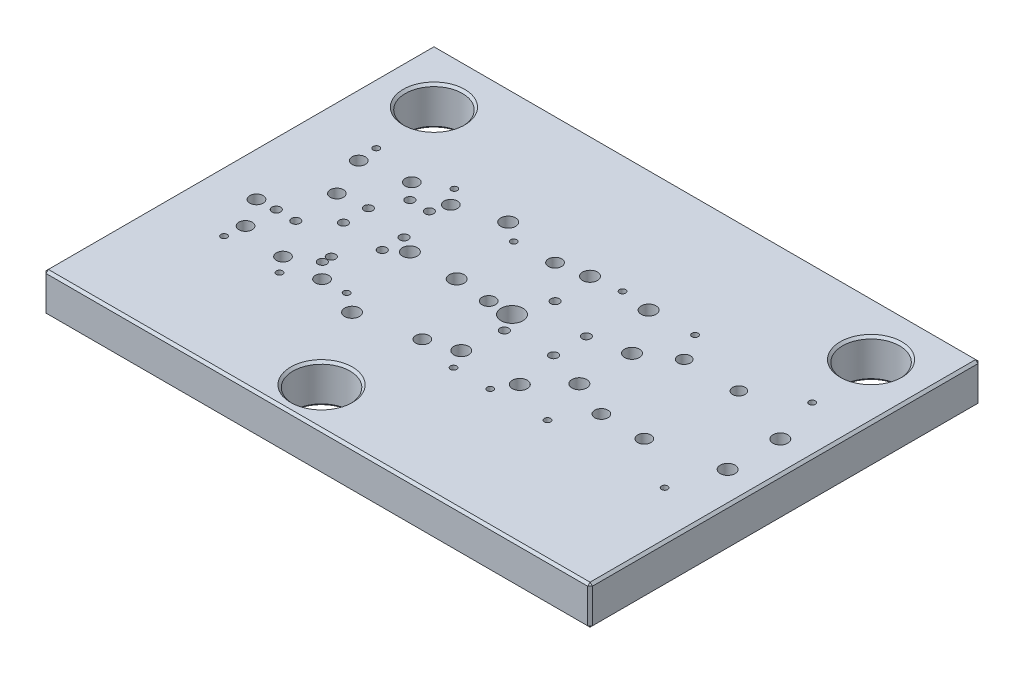
SolidWorks part; units mm, degrees
material "Plain Carbon Steel"
ref_plane "Front Plane" through (0, 0, 0) normal (0, 0, 1) x (1, 0, 0)
ref_plane "Top Plane" through (0, 0, 0) normal (0, 1, 0) x (1, 0, 0)
ref_plane "Right Plane" through (0, 0, 0) normal (1, 0, 0) x (0, 0, -1)
sketch "Sketch1" plane through (0, 0, 0) normal (0, 1, 0) x (1, 0, 0)
  line L1 (-350, -250) -> (350, -250)
  line L2 (-350, -250) -> (-350, 250)
  line L3 (-350, 250) -> (350, 250)
  line L4 (350, -250) -> (350, 250)
  line L5 (-350, -250) -> (350, 250) construction
  line L6 (-350, 250) -> (350, -250) construction
  point P0 (0, 0)
  dimension "D1" = 700
  dimension "D2" = 500
extrude "Boss-Extrude1" add sketch "Sketch1" against normal blind 50
sketch "Sketch2" plane through (0, 0, 0) normal (0, 1, 0) x (1, 0, 0)
  line L0 (350, 250) -> (-350, 250) construction
  line L1 (-350, 250) -> (-350, -250) construction
  line L2 (350, -250) -> (350, 250) construction
  line L3 (-350, -250) -> (350, -250) construction
  circle A0 centre (-280, 180) radius 36.5
  circle A1 centre (280, 180) radius 36.5
  circle A2 centre (-44, -200) radius 36.5
  dimension "D1" = 73
  dimension "D2" = 70
  dimension "D3" = 70
  dimension "D4" = 70
  dimension "D5" = 50
  dimension "D6" = 44
extrude "Cut-Extrude1" cut sketch "Sketch2" against normal up to next
chamfer "Chamfer1" distance 3 angle 45 6 edges at (280, -50, -216.5) (280, 0, -143.5) (-280, -50, -216.5) (-280, 0, -143.5) (-44, -50, 163.5) (-44, 0, 236.5)
chamfer "Chamfer2" distance 3 angle 45 12 edges at (-350, -25, -250) (-350, -25, 250) (350, -25, -250) (0, -50, -250) (-350, -50, 0) (0, -50, 250) (350, -50, 0) (350, -25, 250) (350, 0, 0) (0, 0, -250) (-350, 0, 0) (0, 0, 250)
hole_wizard "M30x2.0 Tapped Hole1" positions "Sketch5" profile "Sketch4" tap size "M30x2.0" standard "ISO" end condition through all
sketch "Sketch5" plane through (0, 0, 0) normal (0, 1, 0) x (1, 0, 0)
  point P0 (0, 0)
sketch "Sketch4" plane through (0, 0, 0) normal (1, 0, 0) x (0, 0, 1)
  line L0 (0, 0) -> (0, 50)
  line L1 (0, 50) -> (14, 50)
  line L2 (14, 50) -> (14, 0)
  line L5 (14, 0) -> (0, 0)
  line L11 (0, -6.35) -> (0, 107.95) construction
  dimension "Thru Tap Drill Dia." = 28
  dimension "Thru Tap Drill Depth" = 50
cosmetic thread "Hole Thread1"
sketch "Sketch7" plane through (0, 0, 0) normal (0, 1, 0) x (1, 0, 0)
  circle A0 centre (310, 33.75) radius 6
  circle A1 centre (310, -33.75) radius 6
  circle A2 centre (120, -33.75) radius 6
  circle A3 centre (120, 33.75) radius 6
  dimension "D1" = 12
extrude "Cut-Extrude2" cut sketch "Sketch7" against normal up to next
sketch "Sketch8" plane through (0, 0, 0) normal (0, 1, 0) x (1, 0, 0)
  circle A0 centre (222.63, -53.14) radius 8.5
  circle A1 centre (167.63, -53.14) radius 8.5
  dimension "D1" = 17
extrude "Cut-Extrude3" cut sketch "Sketch8" against normal up to next
sketch "Sketch9" plane through (0, 0, 0) normal (0, 1, 0) x (1, 0, 0)
  circle A0 centre (160.13, 60.5) radius 8
  circle A1 centre (230.13, 60.5) radius 8
  dimension "D1" = 16
extrude "Cut-Extrude4" cut sketch "Sketch9" against normal up to next
sketch "Sketch11" plane through (0, 0, 0) normal (0, 1, 0) x (1, 0, 0)
  circle A0 centre (310, -33.75) radius 9.5
  circle A1 centre (310, 33.75) radius 9.5
  circle A2 centre (120, -33.75) radius 9.5
  circle A3 centre (120, 33.75) radius 9.5
  dimension "D1" = 19
extrude "Cut-Extrude5" cut sketch "Sketch11" against normal blind 36.8
hole_wizard "M10 Tapped Hole1" positions "Sketch14" profile "Sketch13" tap size "M10" standard "ISO"
sketch "Sketch14" plane through (0, -50, 0) normal (0, -1, 0) x (-1, 0, 0)
  point P0 (-307, -94.5)
  point P3 (-123, -94.5)
  point P6 (-123, 94.5)
  point P9 (-307, 94.5)
sketch "Sketch13" plane through (307, -50, 94.5) normal (1, 0, 0) x (0, 0, -1)
  line L0 (0, 0) -> (0, 30.0537)
  line L1 (0, 30.0537) -> (4.25, 27.5)
  line L2 (4.25, 27.5) -> (4.25, 0)
  line L5 (4.25, 0) -> (0, 0)
  line L10 (0, 30.0537) -> (-4.25, 27.5) construction
  line L11 (0, -6.35) -> (0, 107.95) construction
  dimension "Tap Drill Dia." = 8.5
  dimension "Tap Drill Depth" = 27.5
  dimension "Drill Angle" = 118
cosmetic thread "Hole Thread2"
cosmetic thread "Hole Thread3"
cosmetic thread "Hole Thread4"
cosmetic thread "Hole Thread5"
hole_wizard "Ø8.0mm Dowel Hole1" positions "Sketch17" profile "Sketch16" hole size "Ø8.0" standard "ISO" end condition through all
sketch "Sketch17" plane through (0, 0, 0) normal (0, 1, 0) x (1, 0, 0)
  point P0 (290, 94.5)
  point P3 (140, 94.5)
  point P6 (290, -94.5)
  point P9 (140, -94.5)
sketch "Sketch16" plane through (290, 0, -94.5) normal (1, 0, 0) x (0, 0, 1)
  line L0 (0, 0) -> (0, 50)
  line L1 (0, 50) -> (4, 50)
  line L2 (4, 50) -> (4, 0)
  line L5 (4, 0) -> (0, 0)
  line L11 (0, -6.35) -> (0, 107.95) construction
  dimension "Thru Hole Dia." = 8
  dimension "Thru Hole Depth" = 50
hole_wizard "M8 Tapped Hole1" positions "Sketch20" profile "Sketch19" tap size "M8" standard "ISO"
sketch "Sketch20" plane through (0, -50, 0) normal (0, 1, 0) x (1, 0, 0)
  point P0 (62.13, 96.5)
  point P3 (28.13, 96.5)
  point P6 (84.13, -96.5)
  point P9 (6.13, -96.5)
sketch "Sketch19" plane through (62.13, -50, -96.5) normal (1, 0, 0) x (0, 0, -1)
  line L0 (0, 0) -> (0, 24.2929)
  line L1 (0, 24.2929) -> (3.4, 22.25)
  line L2 (3.4, 22.25) -> (3.4, 0)
  line L5 (3.4, 0) -> (0, 0)
  line L10 (0, 24.2929) -> (-3.4, 22.25) construction
  line L11 (0, -6.35) -> (0, 107.95) construction
  dimension "Tap Drill Dia." = 6.8
  dimension "Tap Drill Depth" = 22.25
  dimension "Drill Angle" = 118
cosmetic thread "Hole Thread6"
cosmetic thread "Hole Thread7"
cosmetic thread "Hole Thread8"
cosmetic thread "Hole Thread9"
hole_wizard "Ø8.0mm Dowel Hole2" positions "Sketch23" profile "Sketch22" hole size "Ø8.0" standard "ISO" end condition through all
sketch "Sketch23" plane through (0, 0, 0) normal (0, 1, 0) x (1, 0, 0)
  point P0 (68.63, -96.5)
  point P3 (21.63, -96.5)
  point P6 (45.13, 96.5)
sketch "Sketch22" plane through (68.63, 0, 96.5) normal (1, 0, 0) x (0, 0, 1)
  line L0 (0, 0) -> (0, 50)
  line L1 (0, 50) -> (4, 50)
  line L2 (4, 50) -> (4, 0)
  line L5 (4, 0) -> (0, 0)
  line L11 (0, -6.35) -> (0, 107.95) construction
  dimension "Thru Hole Dia." = 8
  dimension "Thru Hole Depth" = 50
hole_wizard "Ø11.0 (11) Diameter Hole1" positions "Sketch26" profile "Sketch25" hole size "Ø11.0" standard "ISO" end condition through all
sketch "Sketch26" plane through (0, 0, 0) normal (0, 1, 0) x (1, 0, 0)
  point P0 (71.88, -18.64)
  point P3 (12.88, -22.64)
  point P6 (71.88, 23.36)
  point P9 (12.88, 42.36)
sketch "Sketch25" plane through (71.88, 0, 18.64) normal (1, 0, 0) x (0, 0, 1)
  line L0 (0, 0) -> (0, 50)
  line L1 (0, 50) -> (5.5, 50)
  line L2 (5.5, 50) -> (5.5, 0)
  line L5 (5.5, 0) -> (0, 0)
  line L11 (0, -6.35) -> (0, 107.95) construction
  dimension "Thru Hole Dia." = 11
  dimension "Thru Hole Depth" = 50
sketch "Sketch27" plane through (0, 0, 0) normal (0, 1, 0) x (1, 0, 0)
  circle A0 centre (7.63, 92.36) radius 6
  circle A1 centre (82.63, 92.36) radius 6
  circle A2 centre (82.63, -72.64) radius 6
  circle A3 centre (7.63, -72.64) radius 6
  dimension "D1" = 12
extrude "Cut-Extrude6" cut sketch "Sketch27" against normal through all
sketch "Sketch29" plane through (0, 0, 0) normal (0, 1, 0) x (1, 0, 0)
  circle A0 centre (7.63, 92.36) radius 9.5
  circle A1 centre (82.63, 92.36) radius 9.5
  circle A2 centre (7.63, -72.64) radius 9.5
  circle A3 centre (82.63, -72.64) radius 9.5
  dimension "D1" = 19
extrude "Cut-Extrude7" cut sketch "Sketch29" against normal blind 36.8
sketch "Sketch30" plane through (0, 0, 0) normal (0, 1, 0) x (1, 0, 0)
  circle A0 centre (-29.87, 85) radius 5
  circle A1 centre (-29.87, 0) radius 5
  circle A2 centre (-29.87, -85) radius 5
  dimension "D1" = 10
extrude "Cut-Extrude8" cut sketch "Sketch30" against normal through all
sketch "Sketch31" plane through (0, 0, 0) normal (0, 1, 0) x (1, 0, 0)
  circle A0 centre (-29.87, 85) radius 8.5
  circle A1 centre (-29.87, 0) radius 8.5
  circle A2 centre (-29.87, -85) radius 8.5
  dimension "D1" = 17
extrude "Cut-Extrude9" cut sketch "Sketch31" against normal blind 39.8
hole_wizard "M8 Tapped Hole2" positions "Sketch34" profile "Sketch33" tap size "M8" standard "ISO"
sketch "Sketch34" plane through (0, -50, 0) normal (0, -1, 0) x (-1, 0, 0)
  point P0 (79.87, -97.5)
  point P3 (129.87, -97.5)
  point P6 (79.87, 97.5)
  point P9 (129.87, 97.5)
sketch "Sketch33" plane through (-79.87, -50, 97.5) normal (1, 0, 0) x (0, 0, -1)
  line L0 (0, 0) -> (0, 24.2929)
  line L1 (0, 24.2929) -> (3.4, 22.25)
  line L2 (3.4, 22.25) -> (3.4, 0)
  line L5 (3.4, 0) -> (0, 0)
  line L10 (0, 24.2929) -> (-3.4, 22.25) construction
  line L11 (0, -6.35) -> (0, 107.95) construction
  dimension "Tap Drill Dia." = 6.8
  dimension "Tap Drill Depth" = 22.25
  dimension "Drill Angle" = 118
cosmetic thread "Hole Thread10"
cosmetic thread "Hole Thread11"
cosmetic thread "Hole Thread12"
cosmetic thread "Hole Thread13"
hole_wizard "Ø8.0mm Dowel Hole3" positions "Sketch37" profile "Sketch36" hole size "Ø8.0" standard "ISO" end condition through all
sketch "Sketch37" plane through (0, 0, 0) normal (0, 1, 0) x (1, 0, 0)
  point P0 (-79.87, 81.975)
  point P3 (-129.87, -82)
sketch "Sketch36" plane through (-79.87, 0, -81.975) normal (1, 0, 0) x (0, 0, 1)
  line L0 (0, 0) -> (0, 50)
  line L1 (0, 50) -> (4, 50)
  line L2 (4, 50) -> (4, 0)
  line L5 (4, 0) -> (0, 0)
  line L11 (0, -6.35) -> (0, 107.95) construction
  dimension "Thru Hole Dia." = 8
  dimension "Thru Hole Depth" = 50
sketch "Sketch38" plane through (0, 0, 0) normal (0, 1, 0) x (1, 0, 0)
  circle A0 centre (-104.87, 100) radius 6 construction
  circle A1 centre (-104.87, -100) radius 6 construction
  circle A2 centre (-104.87, 100) radius 6
  circle A3 centre (-104.87, -100) radius 6
  circle A4 centre (-74.87, 4) radius 6 construction
  circle A5 centre (-74.87, 4) radius 6
  circle A6 centre (-134.87, 4) radius 6 construction
  circle A7 centre (-134.87, 4) radius 6
extrude "Cut-Extrude10" cut sketch "Sketch38" against normal through all
sketch "Sketch39" plane through (0, 0, 0) normal (0, 1, 0) x (1, 0, 0)
  circle A0 centre (-104.87, 100) radius 9.5
  circle A1 centre (-104.87, -100) radius 9.5
  circle A2 centre (-74.87, 4) radius 9.5
  circle A3 centre (-134.87, 4) radius 9.5
  dimension "D1" = 19
extrude "Cut-Extrude11" cut sketch "Sketch39" against normal blind 36.8
sketch "Sketch40" plane through (0, -50, 0) normal (0, -1, 0) x (1, 0, 0)
  circle A0 centre (-185.87, -82.5) radius 10 construction
  circle A1 centre (-210.87, 82.5) radius 10 construction
  circle A2 centre (-185.87, 82.5) radius 10 construction
  circle A3 centre (-160.87, 82.5) radius 10 construction
  circle A4 centre (-160.87, 33) radius 10 construction
  circle A5 centre (-210.87, 33) radius 10 construction
  circle A6 centre (-160.87, -39) radius 10 construction
  circle A7 centre (-160.87, -82.5) radius 10 construction
  circle A8 centre (-210.87, -82.5) radius 10 construction
  circle A9 centre (-210.87, -47) radius 10 construction
  circle A10 centre (-185.87, -82.5) radius 10
  circle A11 centre (-210.87, 82.5) radius 10
  circle A12 centre (-185.87, 82.5) radius 10
  circle A13 centre (-160.87, 82.5) radius 10
  circle A14 centre (-160.87, 33) radius 10
  circle A15 centre (-210.87, 33) radius 10
  circle A16 centre (-160.87, -39) radius 10
  circle A17 centre (-160.87, -82.5) radius 10
  circle A18 centre (-210.87, -82.5) radius 10
  circle A19 centre (-210.87, -47) radius 10
extrude "Cut-Extrude12" cut sketch "Sketch40" against normal blind 9.2
hole_wizard "Ø10.0 (10) Diameter Hole1" positions "Sketch44" profile "Sketch43" hole size "Ø10.0" standard "ISO" end condition through all
sketch "Sketch44" plane through (0, 0, 0) normal (0, 1, 0) x (1, 0, 0)
  point P0 (-160.87, 82.5)
  point P3 (-210.87, 82.5)
  point P6 (-160.87, -82.5)
  point P9 (-210.87, -82.5)
sketch "Sketch43" plane through (-160.87, 0, -82.5) normal (1, 0, 0) x (0, 0, 1)
  line L0 (0, 0) -> (0, 50)
  line L1 (0, 50) -> (5, 50)
  line L2 (5, 50) -> (5, 0)
  line L5 (5, 0) -> (0, 0)
  line L11 (0, -6.35) -> (0, 107.95) construction
  dimension "Thru Hole Dia." = 10
  dimension "Thru Hole Depth" = 50
sketch "Sketch45" plane through (0, 0, 0) normal (0, 1, 0) x (1, 0, 0)
  circle A0 centre (-160.87, 82.5) radius 8.5
  circle A1 centre (-210.87, 82.5) radius 8.5
  circle A2 centre (-160.87, -82.5) radius 8.5
  circle A3 centre (-210.87, -82.5) radius 8.5
  dimension "D1" = 17
extrude "Cut-Extrude13" cut sketch "Sketch45" against normal blind 33.8
hole_wizard "Ø11.0 (11) Diameter Hole2" positions "Sketch48" profile "Sketch47" hole size "Ø11.0" standard "ISO" end condition through all
sketch "Sketch48" plane through (0, 0, 0) normal (0, 1, 0) x (1, 0, 0)
  point P0 (-167.37, 61.5)
  point P3 (-192.37, 61.5)
  point P6 (-154.62, 16.36)
  point P9 (-209.87, 25.86)
  point P12 (-209.87, -6.14)
  point P15 (-179.87, -51.64)
  point P20 (-179.87, -63.14)
  point P23 (-154.62, -11.64)
sketch "Sketch47" plane through (-167.37, 0, -61.5) normal (1, 0, 0) x (0, 0, 1)
  line L0 (0, 0) -> (0, 50)
  line L1 (0, 50) -> (5.5, 50)
  line L2 (5.5, 50) -> (5.5, 0)
  line L5 (5.5, 0) -> (0, 0)
  line L11 (0, -6.35) -> (0, 107.95) construction
  dimension "Thru Hole Dia." = 11
  dimension "Thru Hole Depth" = 50
hole_wizard "M8 Tapped Hole3" positions "Sketch53" profile "Sketch52" tap size "M8" standard "ISO"
sketch "Sketch53" plane through (0, -50, 0) normal (0, -1, 0) x (-1, 0, 0)
  point P0 (160.87, -102.5)
  point P3 (210.87, -102.5)
  point P6 (160.87, 102.5)
  point P9 (210.87, 102.5)
sketch "Sketch52" plane through (-160.87, -50, 102.5) normal (1, 0, 0) x (0, 0, -1)
  line L0 (0, 0) -> (0, 24.2929)
  line L1 (0, 24.2929) -> (3.4, 22.25)
  line L2 (3.4, 22.25) -> (3.4, 0)
  line L5 (3.4, 0) -> (0, 0)
  line L10 (0, 24.2929) -> (-3.4, 22.25) construction
  line L11 (0, -6.35) -> (0, 107.95) construction
  dimension "Tap Drill Dia." = 6.8
  dimension "Tap Drill Depth" = 22.25
  dimension "Drill Angle" = 118
cosmetic thread "Hole Thread14"
cosmetic thread "Hole Thread15"
cosmetic thread "Hole Thread16"
cosmetic thread "Hole Thread17"
hole_wizard "Ø8.0mm Dowel Hole4" positions "Sketch56" profile "Sketch55" hole size "Ø8.0" standard "ISO" end condition through all
sketch "Sketch56" plane through (0, 0, 0) normal (0, 1, 0) x (1, 0, 0)
  point P0 (-176.37, 102.5)
  point P3 (-195.37, -102.5)
sketch "Sketch55" plane through (-176.37, 0, -102.5) normal (1, 0, 0) x (0, 0, 1)
  line L0 (0, 0) -> (0, 50)
  line L1 (0, 50) -> (4, 50)
  line L2 (4, 50) -> (4, 0)
  line L5 (4, 0) -> (0, 0)
  line L11 (0, -6.35) -> (0, 107.95) construction
  dimension "Thru Hole Dia." = 8
  dimension "Thru Hole Depth" = 50
sketch "Sketch57" plane through (0, 0, 0) normal (0, 1, 0) x (1, 0, 0)
  circle A0 centre (-268.87, -72.5) radius 5 construction
  circle A1 centre (-291.37, -36) radius 5 construction
  circle A2 centre (-246.37, 22) radius 5 construction
  circle A3 centre (-268.87, 72.5) radius 5 construction
  circle A4 centre (-268.87, -72.5) radius 5
  circle A5 centre (-291.37, -36) radius 5
  circle A6 centre (-246.37, 22) radius 5
  circle A7 centre (-268.87, 72.5) radius 5
extrude "Cut-Extrude14" cut sketch "Sketch57" against normal through all
sketch "Sketch58" plane through (0, 0, 0) normal (0, 1, 0) x (1, 0, 0)
  circle A0 centre (-268.87, 72.5) radius 8.5
  circle A1 centre (-246.37, 22) radius 8.5
  circle A2 centre (-291.37, -36) radius 8.5
  circle A3 centre (-268.87, -72.5) radius 8.5
  dimension "D1" = 17
extrude "Cut-Extrude15" cut sketch "Sketch58" against normal blind 36.8
hole_wizard "Ø11.0 (11) Diameter Hole3" positions "Sketch61" profile "Sketch60" hole size "Ø11.0" standard "ISO" end condition through all
sketch "Sketch61" plane through (0, 0, 0) normal (0, 1, 0) x (1, 0, 0)
  point P0 (-267.37, -34.64)
  point P3 (-242.37, -34.64)
sketch "Sketch60" plane through (-267.37, 0, 34.64) normal (1, 0, 0) x (0, 0, 1)
  line L0 (0, 0) -> (0, 50)
  line L1 (0, 50) -> (5.5, 50)
  line L2 (5.5, 50) -> (5.5, 0)
  line L5 (5.5, 0) -> (0, 0)
  line L11 (0, -6.35) -> (0, 107.95) construction
  dimension "Thru Hole Dia." = 11
  dimension "Thru Hole Depth" = 50
hole_wizard "M8 Tapped Hole4" positions "Sketch64" profile "Sketch63" tap size "M8" standard "ISO"
sketch "Sketch64" plane through (0, -50, 0) normal (0, 1, 0) x (1, 0, 0)
  point P0 (-291.37, 97.5)
  point P3 (-251.37, 97.5)
  point P6 (-251.37, -97.5)
  point P9 (-291.37, -97.5)
sketch "Sketch63" plane through (-291.37, -50, -97.5) normal (1, 0, 0) x (0, 0, -1)
  line L0 (0, 0) -> (0, 24.2929)
  line L1 (0, 24.2929) -> (3.4, 22.25)
  line L2 (3.4, 22.25) -> (3.4, 0)
  line L5 (3.4, 0) -> (0, 0)
  line L10 (0, 24.2929) -> (-3.4, 22.25) construction
  line L11 (0, -6.35) -> (0, 107.95) construction
  dimension "Tap Drill Dia." = 6.8
  dimension "Tap Drill Depth" = 22.25
  dimension "Drill Angle" = 118
cosmetic thread "Hole Thread18"
cosmetic thread "Hole Thread19"
cosmetic thread "Hole Thread20"
cosmetic thread "Hole Thread21"
hole_wizard "Ø8.0mm Dowel Hole5" positions "Sketch67" profile "Sketch66" hole size "Ø8.0" standard "ISO" end condition through all
sketch "Sketch67" plane through (0, 0, 0) normal (0, 1, 0) x (1, 0, 0)
  point P0 (-271.37, -97.5)
  point P3 (-271.37, 97.5)
sketch "Sketch66" plane through (-271.37, 0, 97.5) normal (1, 0, 0) x (0, 0, 1)
  line L0 (0, 0) -> (0, 50)
  line L1 (0, 50) -> (4, 50)
  line L2 (4, 50) -> (4, 0)
  line L5 (4, 0) -> (0, 0)
  line L11 (0, -6.35) -> (0, 107.95) construction
  dimension "Thru Hole Dia." = 8
  dimension "Thru Hole Depth" = 50
hole_wizard "M10 Tapped Hole2" positions "Sketch71" profile "Sketch69" tap size "M10" standard "ISO"
sketch "Sketch71" plane through (0, -50, 0) normal (0, -1, 0) x (-1, 0, 0)
  point P0 (-300, -190)
  point P4 (190, 190)
sketch "Sketch69" plane through (300, -50, 190) normal (1, 0, 0) x (0, 0, -1)
  line L0 (0, 0) -> (0, 30.0537)
  line L1 (0, 30.0537) -> (4.25, 27.5)
  line L2 (4.25, 27.5) -> (4.25, 0)
  line L5 (4.25, 0) -> (0, 0)
  line L10 (0, 30.0537) -> (-4.25, 27.5) construction
  line L11 (0, -6.35) -> (0, 107.95) construction
  dimension "Tap Drill Dia." = 8.5
  dimension "Tap Drill Depth" = 27.5
  dimension "Drill Angle" = 118
cosmetic thread "Hole Thread22"
cosmetic thread "Hole Thread23"
